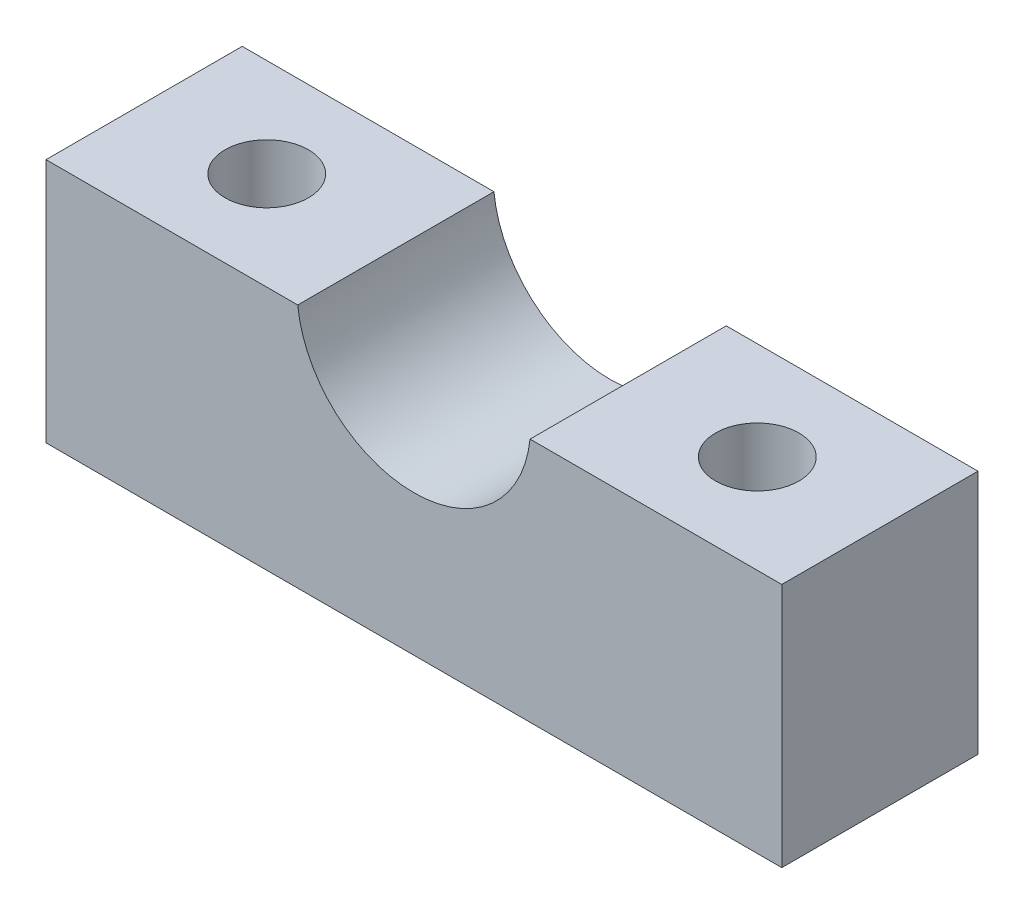
SolidWorks part; units mm, degrees
ref_plane "Front" through (0, 0, 0) normal (0, 0, 1) x (1, 0, 0)
ref_plane "Top" through (0, 0, 0) normal (0, 1, 0) x (1, 0, 0)
ref_plane "Right" through (0, 0, 0) normal (1, 0, 0) x (0, 0, -1)
sketch "Sketch1" plane through (0, 0, 0) normal (0, 1, 0) x (1, 0, 0)
  line L1 (-15, 4) -> (15, 4)
  line L2 (-15, 4) -> (-15, -4)
  line L3 (-15, -4) -> (15, -4)
  line L4 (15, 4) -> (15, -4)
  line L5 (-15, 4) -> (15, -4) construction
  line L6 (-15, -4) -> (15, 4) construction
  point P0 (0, 0)
  dimension "D1" = 8
  dimension "D2" = 30
extrude "Boss-Extrude1" add sketch "Sketch1" against normal blind 10
sketch "Sketch3" plane through (0, 0, 0) normal (0, 1, 0) x (1, 0, 0)
  line L0 (-10, 0) -> (10, 0) construction
  dimension "D1" = 20
hole_wizard "M3 Clearance Hole1" positions "Sketch5" profile "Sketch7" hole size "M3" standard "Ansi Metric" end condition through all
sketch "Sketch5" plane through (0, 0, 0) normal (0, 1, 0) x (-1, 0, 0)
  point P0 (10, 0)
  point P1 (-10, 0)
sketch "Sketch7" plane through (-10, 0, 0) normal (1, 0, 0) x (0, 0, 1)
  line L0 (0, 0) -> (0, 10)
  line L1 (0, 10) -> (1.7, 10)
  line L2 (1.7, 10) -> (1.7, 0)
  line L5 (1.7, 0) -> (0, 0)
  line L11 (0, -6.35) -> (0, 107.95) construction
  dimension "Thru Hole Dia." = 3.4
  dimension "Thru Hole Depth" = 10
sketch "Sketch2" plane through (0, 0, 4) normal (0, 0, 1) x (1, 0, 0)
  line L0 (0, 0.5) -> (0, 0) construction
  line L1 (-15, 0) -> (15, 0) construction
  line L2 (-4.7362, 0) -> (4.7362, 0)
  arc A0 (-4.7362, 0) -> (4.7362, 0) centre (0, 0.5) ccw
  dimension "D2" = 9.525
  dimension "D1" = 0.5
extrude "Cut-Extrude1" cut sketch "Sketch2" against normal through all
